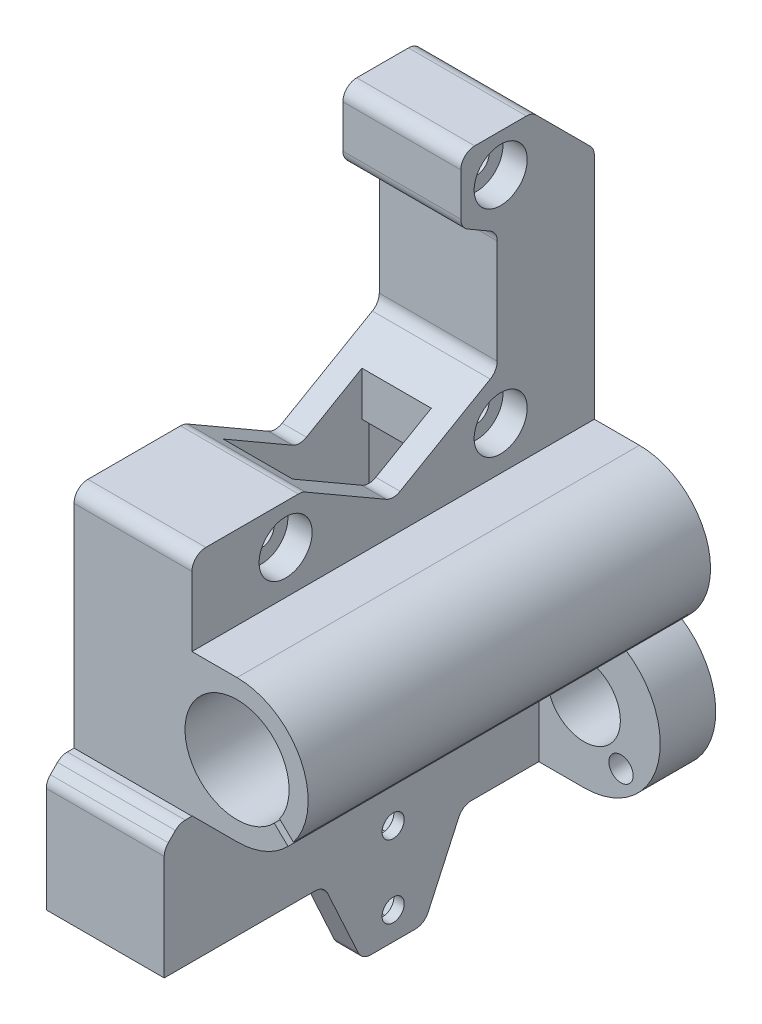
SolidWorks part; units mm, degrees
ref_plane "Front Plane" through (0, 0, 0) normal (0, 0, 1) x (1, 0, 0)
ref_plane "Top Plane" through (0, 0, 0) normal (0, 1, 0) x (1, 0, 0)
ref_plane "Right Plane" through (0, 0, 0) normal (1, 0, 0) x (0, 0, -1)
ref_plane "Plane1" through (50, 0, 0) normal (1, 0, 0) x (0, 0, -1)
sketch "Sketch1" plane through (50, 0, 0) normal (1, 0, 0) x (0, 0, -1)
  line L0 (-62, -12.5) -> (-59.8, -10.3)
  line L1 (-62, -28.5) -> (0, -28.5)
  line L2 (-62, -28.5) -> (-62, -12.5)
  line L3 (-19.244, 53) -> (-8.9612, 53)
  line L4 (0, -28.5) -> (0, 44.0388)
  line L5 (-59.8, -10.3) -> (-58, -10.3)
  line L6 (-58, -10.3) -> (-58, 22.2516)
  line L9 (-58, 22.2516) -> (-42.1152, 22.2516)
  line L10 (-8.9612, 53) -> (0, 44.0388)
  line L11 (-19.244, 53) -> (-19.244, 43.6879)
  line L13 (-29, 14.6795) -> (-14, 23.3397)
  line L14 (-14, 23.3397) -> (-14, 40.6603)
  line L15 (-14, 40.6603) -> (-19.244, 43.6879)
  line L18 (-42.1152, 22.2516) -> (-29, 14.6795)
  line L19 (-42, -12.5) -> (-16, -12.5)
  line L20 (-42, -12.5) -> (-42, -11)
  line L21 (-42, -11) -> (-16, -11)
  line L22 (-16, -12.5) -> (-16, -11)
  line L23 (-38.5473, 43.8084) -> (-46.1398, 39.4248) [skipped]
  line L24 (-44, 29.636) -> (-44, 20.8689) [skipped]
  circle A0 centre (-44.5, 16.5) radius 1.825
  circle A1 centre (-29, 32) radius 15 construction
  circle A2 centre (-13.5, 16.5) radius 1.825
  circle A3 centre (-13.5, 47.5) radius 1.825
  point P21 (-29, -11)
  dimension "D3" = 3.65
  dimension "D4" = 30
  dimension "D1" = 31
  dimension "D2" = 31
  dimension "D5" = 1.5
  dimension "D6" = 16
  dimension "D7" = 26
  dimension "D8" = 29
  dimension "D9" = 21
  dimension "D10" = 15.5
  dimension "D11" = 15.5
extrude "Boss-Extrude1" add sketch "Sketch1" along normal blind 17 separate body
sketch "Sketch8" plane through (0, 0, 58) normal (0, 0, 1) x (1, 0, 0)
  line L0 (67, -28.5) -> (50, -28.5) construction
  line L3 (67, 22.2516) -> (67, -10.3) construction
  line L4 (73.5, 10.25) -> (67, 10.25)
  line L5 (67, 10.25) -> (67, -10.25)
  line L6 (67, -10.25) -> (73.5, -10.25)
  line L7 (67, 10.25) -> (67, -10.25)
  arc A3 (73.5, -10.25) -> (73.5, 10.25) centre (73.5, 0) ccw
  line M3 (67, -10.3) -> (67, 22.2516)
  dimension "D1" = 6.5
  dimension "D2" = 28.5
  dimension "D3" = 10.25
extrude "Boss-Extrude2" add sketch "Sketch8" against normal up to surface (58 mm away) contours L6 A3 L4 M3 up to face at (58.5, 7.7694, 0)
sketch "Sketch17" plane through (67, 0, 0) normal (1, 0, 0) x (0, 0, -1)
  line L0 (-33.5, -40.5) -> (-39, -28.5)
  line L1 (-62, -28.5) -> (0, -28.5) construction
  line L2 (-39, -28.5) -> (-19, -28.5)
  line L3 (-19, -28.5) -> (-24.5, -40.5)
  line L4 (-24.5, -40.5) -> (-33.5, -40.5)
  line L5 (-62, -28.5) -> (0, -28.5) construction
  line L6 (0, -28.5) -> (0, -10.25) construction
  point P10 (-29, -28.5)
  dimension "D1" = 9
  dimension "D2" = 12
  dimension "D3" = 20
  dimension "D4" = 29
extrude "Boss-Extrude4" add sketch "Sketch17" against normal blind 3.5
sketch "Sketch9" plane through (0, 0, 58) normal (0, 0, 1) x (1, 0, 0)
  circle A0 centre (73.5, 0) radius 7.5
  dimension "D1" = 15
extrude "Cut-Extrude5" cut sketch "Sketch9" against normal blind 61
sketch "Sketch18" plane through (67, 0, 0) normal (1, 0, 0) x (0, 0, -1)
  line L0 (-33.5, -40.5) -> (-24.5, -40.5) construction
  line L1 (-33.5, -40.5) -> (-24.5, -40.5) construction
  line L2 (-29, -40.5) -> (-29, -26) construction
  circle A0 centre (-29, -36.5) radius 1.6
  circle A2 centre (-29, -26) radius 1.6
  dimension "D3" = 3.2
  dimension "D1" = 10.5
  dimension "D2" = 4
extrude "Cut-Extrude12" cut sketch "Sketch18" against normal blind 5.5
sketch "Sketch19" plane through (67, 0, 0) normal (-1, 0, 0) x (0, 0, 1)
  line L1 (30.7609, -33.45) -> (27.2391, -33.45)
  line L2 (27.2391, -33.45) -> (25.4782, -36.5)
  line L3 (25.4782, -36.5) -> (27.2391, -39.55)
  line L4 (27.2391, -39.55) -> (30.7609, -39.55)
  line L5 (30.7609, -39.55) -> (32.5218, -36.5)
  line L6 (32.5218, -36.5) -> (30.7609, -33.45)
  line L7 (32.5218, -26) -> (30.7609, -22.95)
  line L8 (30.7609, -22.95) -> (27.2391, -22.95)
  line L9 (27.2391, -22.95) -> (25.4782, -26)
  line L10 (25.4782, -26) -> (27.2391, -29.05)
  line L11 (27.2391, -29.05) -> (30.7609, -29.05)
  line L12 (30.7609, -29.05) -> (32.5218, -26)
  circle A0 centre (29, -36.5) radius 3.05 construction
  circle A1 centre (29, -26) radius 3.05 construction
  dimension "D1" = 6.1
extrude "Cut-Extrude13" cut sketch "Sketch19" along normal blind 3.5 from offset 1.5
fillet "Fillet1" radius 2 15 edges at (58.5, 22.2516, 42.1152) (58.5, 44.0388, 0) (58.5, 53, 8.9612) (58.5, 53, 19.244) (58.5, 43.6879, 19.244) (58.5, 14.6795, 29) (58.5, 23.3397, 14) (58.5, 40.6603, 14) (58.5, -10.3, 59.8) (65.25, -40.5, 24.5) (65.25, -28.5, 19) (65.25, -28.5, 39) (65.25, -40.5, 33.5) (58.5, 22.2516, 58) (58.5, -12.5, 62)
sketch "Sketch3" plane through (0, 22.2516, 0) normal (0, 1, 0) x (1, 0, 0)
  line L1 (53.5, -40) -> (63.5, -40)
  line L2 (53.5, -40) -> (53.5, -20)
  line L3 (53.5, -20) -> (63.5, -20)
  line L4 (63.5, -40) -> (63.5, -20)
  line L5 (50, -55) -> (50, 55) construction
  line L6 (67, 0) -> (67, -58) construction
  line L7 (67, 0) -> (50, 0) construction
  dimension "D1" = 3.5
  dimension "D2" = 3.5
  dimension "D3" = 20
  dimension "D5" = 20
extrude "Cut-Extrude1" cut sketch "Sketch3" against normal blind 13
sketch "Sketch4" plane through (0, -28.5, 0) normal (0, -1, 0) x (1, 0, 0)
  line L0 (50, -55) -> (50, 55) construction
  line L1 (67, 0) -> (50, 0) construction
  line L15 (53.5, 19) -> (56.5711, 16)
  line L16 (56.5711, 16) -> (60.5, 16)
  line L17 (60.5, 16) -> (63.5, 19.0711)
  line L18 (63.5, 19.0711) -> (63.5, 36)
  line L19 (63.5, 36) -> (61.4548, 42)
  line L20 (61.4548, 42) -> (55.5452, 42)
  line L21 (55.5452, 42) -> (53.5, 36)
  line L22 (53.5, 36) -> (53.5, 19)
  line L23 (67, 62) -> (67, 40.2834) construction
  point P2 (58.5356, 16)
  dimension "D1" = 3.5
  dimension "D2" = 3.5
  dimension "D3" = 6
  dimension "D4" = 16
  dimension "D5" = 26
  dimension "D6" = 3
extrude "Cut-Extrude2" cut sketch "Sketch4" against normal blind 42 contours L15 L16 L17 L18 L19 L20 L21 L22
sketch "Sketch5" plane through (67, 0, 0) normal (1, 0, 0) x (0, 0, -1)
  circle A0 centre (-13.5, 16.5) radius 3.825
  circle A1 centre (-44.5, 16.5) radius 3.825
  circle A2 centre (-13.5, 47.5) radius 0.0001
  circle A3 centre (-13.5, 47.5) radius 3.825
  dimension "D1" = 7.65
extrude "Cut-Extrude3" cut sketch "Sketch5" against normal blind 3.5
sketch "Sketch7" plane through (0, -28.5, 0) normal (0, -1, 0) x (1, 0, 0)
  line L0 (56.7517, 54.6809) -> (57.1299, 55.738)
  line L1 (57.1299, 55.738) -> (59.92, 55.738)
  line L2 (59.92, 55.738) -> (60.2691, 54.6709)
  line L3 (67, 0) -> (50, 0) construction
  line L4 (50, 62) -> (50, 0) construction
  line L5 (56.7517, 9.6809) -> (57.1299, 10.738)
  line L6 (57.1299, 10.738) -> (59.92, 10.738)
  line L7 (59.92, 10.738) -> (60.2691, 9.6709)
  line L8 (67, 17.7166) -> (67, 0) construction
  arc A0 (56.7517, 54.6809) -> (60.2691, 54.6709) centre (58.5, 51) ccw
  arc A2 (56.7517, 9.6809) -> (60.2691, 9.6709) centre (58.5, 6) ccw
  dimension "D2" = 4.075
  dimension "D1" = 17
  dimension "D3" = 6
  dimension "D4" = 45
  dimension "D5" = 8.5
extrude "Cut-Extrude4" cut sketch "Sketch7" against normal blind 38
sketch "Sketch11" plane through (0, 0, 0) normal (0, 0, -1) x (-1, 0, 0)
  line L0 (-67, -28.5) -> (-50, -28.5) construction
  line L1 (-73.5, -28.5) -> (-67, -28.5)
  line L2 (-73.5, -17.5) -> (-83.3811, -28.233) construction
  line L4 (-67, -28.5) -> (-67, -7.7324)
  line L5 (-78.5591, -7.7324) -> (-67, -7.7324)
  arc A0 (-78.5591, -7.7324) -> (-73.5, -28.5) centre (-73.5, -17.5) ccw
  circle A1 centre (-73.5, -17.5) radius 5.25
  circle A3 centre (-73.5, -17.5) radius 8 construction
  point P2 (-73.5, 0)
  dimension "D1" = 22
  dimension "D2" = 10.5
  dimension "D3" = 16
  dimension "D4" = 6.5
extrude "Boss-Extrude3" add sketch "Sketch11" against normal blind 8
sketch "Sketch10" plane through (0, 0, 58) normal (0, 0, 1) x (1, 0, 0)
  line L0 (81.0723, -7.3532) -> (78.4403, -4.8406)
  line L1 (79.2798, -3.983) -> (81.8576, -6.4439)
  line L2 (81.0723, -7.3532) -> (81.8576, -6.4439)
  line L3 (79.2798, -3.983) -> (78.4403, -4.8406)
  dimension "D1" = 1.2
extrude "Cut-Extrude6" cut sketch "Sketch10" against normal blind 57
sketch "Sketch12" plane through (0, 0, 0) normal (0, 0, -1) x (-1, 0, 0)
  line L0 (-73.5043, -17.5048) -> (-68.8655, -12.3295) construction
  circle A1 centre (-73.5, -17.5) radius 8 construction
  circle A2 centre (-68.1603, -11.5428) radius 1.75
  circle A3 centre (-78.8397, -23.4572) radius 1.75
  point P5 (-73.5, -17.5)
  dimension "D1" = 16
  dimension "D2" = 3.5
extrude "Cut-Extrude9" cut sketch "Sketch12" against normal blind 10
sketch "Sketch13" plane through (0, 0, 8) normal (0, 0, 1) x (1, 0, 0)
  line L1 (82.3899, -23.5133) -> (80.6634, -20.4106)
  line L2 (80.6634, -20.4106) -> (77.1131, -20.3545)
  line L3 (77.1131, -20.3545) -> (75.2894, -23.401)
  line L4 (75.2894, -23.401) -> (77.0159, -26.5037)
  line L5 (77.0159, -26.5037) -> (80.5662, -26.5599)
  line L6 (80.5662, -26.5599) -> (82.3899, -23.5133)
  line L7 (67.3519, -15.0003) -> (70.7503, -13.9717)
  line L8 (70.7503, -13.9717) -> (71.5588, -10.5143)
  line L9 (71.5588, -10.5143) -> (68.9688, -8.0854)
  line L10 (68.9688, -8.0854) -> (65.5703, -9.1139)
  line L11 (65.5703, -9.1139) -> (64.7619, -12.5714)
  line L12 (64.7619, -12.5714) -> (67.3519, -15.0003)
  circle A0 centre (78.8397, -23.4572) radius 3.075 construction
  circle A1 centre (68.1603, -11.5428) radius 3.075 construction
  dimension "D1" = 6.15
extrude "Cut-Extrude10" cut sketch "Sketch13" along normal blind 3
sketch "Sketch20" plane through (0, 9.5, 0) normal (0, -1, 0) x (1, 0, 0)
  circle A0 centre (58.5, 6) radius 4.738
  circle A1 centre (58.5, 51) radius 4.738
extrude "Cut-Extrude14" cut sketch "Sketch20" along normal blind 5
